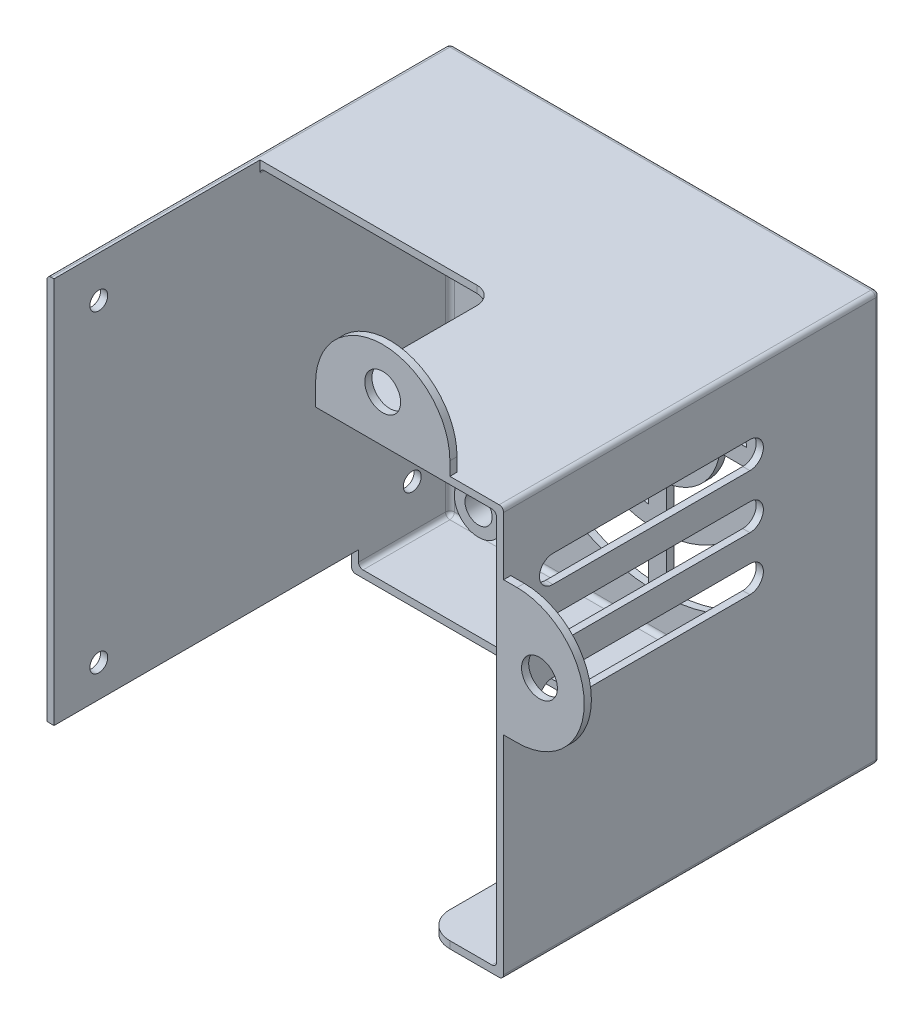
SolidWorks part; units mm, degrees
material "Aleación 1060"
ref_plane "Alzado" through (0, 0, 0) normal (0, 0, 1) x (1, 0, 0)
ref_plane "Planta" through (0, 0, 0) normal (0, 1, 0) x (1, 0, 0)
ref_plane "Vista lateral" through (0, 0, 0) normal (1, 0, 0) x (0, 0, -1)
ref_plane "Plano1" through (0, 0, 42) normal (0, 0, 1) x (1, 0, 0)
sketch "Croquis1" plane through (0, 0, 42) normal (0, 0, 1) x (1, 0, 0)
  line L0 (22.5, 23.6) -> (-25.5, 23.6)
  line L1 (-25.5, 23.6) -> (-25.5, -22.1)
  line L2 (-25.5, -22.1) -> (22.5, -22.1)
  line L3 (22.5, -22.1) -> (22.5, 23.6)
extrude "Saliente-Extruir1" add sketch "Croquis1" against normal blind 42
sketch "Croquis2" plane through (0, 23.6, 0) normal (0, 1, 0) x (-1, 0, 0)
  line L0 (25.5, 42) -> (-1.5, 42)
  line L1 (-1.5, 42) -> (-1.5, 22)
  line L2 (-1.5, 22) -> (25.5, 22)
  line L3 (25.5, 22) -> (25.5, 42)
extrude "Cortar-Extruir1" cut sketch "Croquis2" against normal through all
sketch "Croquis3" plane through (0, 0, 22) normal (0, 0, 1) x (1, 0, 0)
  line L0 (-25.5, 23.6) -> (-24.7, 23.6)
  line L1 (-24.7, 23.6) -> (-24.7, -19.6)
  line L2 (-24.7, -19.6) -> (-25.5, -19.6)
  line L3 (-25.5, -19.6) -> (-25.5, 23.6)
extrude "Saliente-Extruir2" add sketch "Croquis3" along normal blind 23
sketch "Croquis4" plane through (0, 0, 22) normal (0, 0, 1) x (1, 0, 0)
  line L0 (1.5, -22.1) -> (1.5, -19.6)
  line L1 (1.5, -19.6) -> (-25.5, -19.6)
  line L2 (-25.5, -19.6) -> (-25.5, -22.1)
  line L3 (-25.5, -22.1) -> (1.5, -22.1)
extrude "Cortar-Extruir2" cut sketch "Croquis4" against normal blind 11
ref_plane "Plano2" through (0, -19.6, 0) normal (0, -1, 0) x (1, 0, 0)
ref_plane "Plano3" through (0, 22.8, 0) normal (0, 1, 0) x (1, 0, 0)
sketch "Croquis6" plane through (0, 22.8, 0) normal (0, 1, 0) x (1, 0, 0)
  line L0 (1.5, -22) -> (1.5, -11)
  line L1 (1.5, -11) -> (-24.7, -11)
  line L2 (-24.7, -11) -> (-24.7, -22)
  line L3 (-24.7, -22) -> (1.5, -22)
extrude "Cortar-Extruir3" cut sketch "Croquis6" against normal up to surface up to plane "Plano2"
sketch "Croquis7" plane through (1.5, 0, 0) normal (-1, 0, 0) x (0, 0, 1)
  line L0 (42, 22.8) -> (11, 22.8)
  line L1 (11, 22.8) -> (11, -22.1)
  line L2 (11, -22.1) -> (42, -22.1)
  line L3 (42, -22.1) -> (42, 22.8)
extrude "Cortar-Extruir4" cut sketch "Croquis7" against normal blind 12
sketch "Croquis8" plane through (0, 0, 11) normal (0, 0, 1) x (1, 0, 0)
  line L0 (-24.7, -21.3) -> (13.5, -21.3)
  line L1 (13.5, -21.3) -> (13.5, 22.8)
  line L2 (13.5, 22.8) -> (-24.7, 22.8)
  line L3 (-24.7, 22.8) -> (-24.7, -21.3)
extrude "Cortar-Extruir5" cut sketch "Croquis8" against normal blind 10.2
ref_plane "Plano4" through (21.7, 0, 0) normal (1, 0, 0) x (0, 0, -1)
sketch "Croquis9" plane through (21.7, 0, 0) normal (1, 0, 0) x (0, 0, -1)
  line L0 (-0.8, -21.3) -> (-0.8, 22.8)
  line L1 (-0.8, 22.8) -> (-42, 22.8)
  line L2 (-42, 22.8) -> (-42, -21.3)
  line L3 (-42, -21.3) -> (-0.8, -21.3)
extrude "Cortar-Extruir6" cut sketch "Croquis9" against normal up to next
sketch "Croquis10" plane through (0, 0, 0.8) normal (0, 0, 1) x (1, 0, 0)
  line L0 (-0.5, -6.1782) -> (-0.5, -9.1999)
  line L1 (8.4499, -0.25) -> (5.4282, -0.25)
  arc A0 (5.4282, -0.25) -> (-0.5, -6.1782) centre (-1.5, 0.75) cw
  arc A1 (-0.5, -9.1999) -> (8.4499, -0.25) centre (-1.5, 0.75) ccw
extrude "Cortar-Extruir7" cut sketch "Croquis10" against normal through all
sketch "Croquis11" plane through (0, 0, 0.8) normal (0, 0, 1) x (1, 0, 0)
  line L0 (-0.5, -11.2083) -> (-0.5, -17.2222)
  line L1 (16.4722, -0.25) -> (10.4583, -0.25)
  arc A0 (10.4583, -0.25) -> (-0.5, -11.2083) centre (-1.5, 0.75) cw
  arc A1 (-0.5, -17.2222) -> (16.4722, -0.25) centre (-1.5, 0.75) ccw
extrude "Cortar-Extruir8" cut sketch "Croquis11" against normal through all
sketch "Croquis12" plane through (0, 0, 0.8) normal (0, 0, 1) x (1, 0, 0)
  line L0 (-8.4282, -0.25) -> (-11.4499, -0.25)
  line L1 (-2.5, -9.1999) -> (-2.5, -6.1782)
  arc A0 (-2.5, -6.1782) -> (-8.4282, -0.25) centre (-1.5, 0.75) cw
  arc A1 (-11.4499, -0.25) -> (-2.5, -9.1999) centre (-1.5, 0.75) ccw
extrude "Cortar-Extruir9" cut sketch "Croquis12" against normal through all
sketch "Croquis13" plane through (0, 0, 0.8) normal (0, 0, 1) x (1, 0, 0)
  line L0 (-13.4583, -0.25) -> (-19.4722, -0.25)
  line L1 (-2.5, -17.2222) -> (-2.5, -11.2083)
  arc A0 (-2.5, -11.2083) -> (-13.4583, -0.25) centre (-1.5, 0.75) cw
  arc A1 (-19.4722, -0.25) -> (-2.5, -17.2222) centre (-1.5, 0.75) ccw
extrude "Cortar-Extruir10" cut sketch "Croquis13" against normal through all
sketch "Croquis14" plane through (0, 0, 0.8) normal (0, 0, 1) x (1, 0, 0)
  line L0 (-2.5, 7.6782) -> (-2.5, 10.6999)
  line L1 (-11.4499, 1.75) -> (-8.4282, 1.75)
  arc A0 (-8.4282, 1.75) -> (-2.5, 7.6782) centre (-1.5, 0.75) cw
  arc A1 (-2.5, 10.6999) -> (-11.4499, 1.75) centre (-1.5, 0.75) ccw
extrude "Cortar-Extruir11" cut sketch "Croquis14" against normal through all
sketch "Croquis15" plane through (0, 0, 0.8) normal (0, 0, 1) x (1, 0, 0)
  line L0 (-2.5, 12.7083) -> (-2.5, 18.7222)
  line L1 (-19.4722, 1.75) -> (-13.4583, 1.75)
  arc A0 (-13.4583, 1.75) -> (-2.5, 12.7083) centre (-1.5, 0.75) cw
  arc A1 (-2.5, 18.7222) -> (-19.4722, 1.75) centre (-1.5, 0.75) ccw
extrude "Cortar-Extruir12" cut sketch "Croquis15" against normal through all
sketch "Croquis16" plane through (0, 0, 0.8) normal (0, 0, 1) x (1, 0, 0)
  line L0 (5.4282, 1.75) -> (8.4499, 1.75)
  line L1 (-0.5, 10.6999) -> (-0.5, 7.6782)
  arc A0 (-0.5, 7.6782) -> (5.4282, 1.75) centre (-1.5, 0.75) cw
  arc A1 (8.4499, 1.75) -> (-0.5, 10.6999) centre (-1.5, 0.75) ccw
extrude "Cortar-Extruir13" cut sketch "Croquis16" against normal through all
sketch "Croquis17" plane through (22.5, 0, 0) normal (1, 0, 0) x (0, 0, -1)
  line L0 (-36.5, 1.4) -> (-14.5, 1.4)
  line L1 (-14.5, 4.4) -> (-36.5, 4.4)
  arc A0 (-36.5, 4.4) -> (-36.5, 1.4) centre (-36.5, 2.9) ccw
  arc A1 (-14.5, 1.4) -> (-14.5, 4.4) centre (-14.5, 2.9) ccw
extrude "Cortar-Extruir14" cut sketch "Croquis17" against normal up to next
sketch "Croquis18" plane through (22.5, 0, 0) normal (1, 0, 0) x (0, 0, -1)
  line L0 (-36.5, 7.4) -> (-14.5, 7.4)
  line L1 (-14.5, 10.4) -> (-36.5, 10.4)
  arc A0 (-36.5, 10.4) -> (-36.5, 7.4) centre (-36.5, 8.9) ccw
  arc A1 (-14.5, 7.4) -> (-14.5, 10.4) centre (-14.5, 8.9) ccw
extrude "Cortar-Extruir15" cut sketch "Croquis18" against normal up to next
sketch "Croquis19" plane through (22.5, 0, 0) normal (1, 0, 0) x (0, 0, -1)
  line L0 (-36.5, 13.4) -> (-14.5, 13.4)
  line L1 (-14.5, 16.4) -> (-36.5, 16.4)
  arc A0 (-36.5, 16.4) -> (-36.5, 13.4) centre (-36.5, 14.9) ccw
  arc A1 (-14.5, 13.4) -> (-14.5, 16.4) centre (-14.5, 14.9) ccw
extrude "Cortar-Extruir16" cut sketch "Croquis19" against normal up to next
sketch "Croquis20" plane through (0, 0, 0) normal (0, 0, -1) x (-1, 0, 0)
  line L0 (-16.4722, 1.75) -> (-10.4583, 1.75)
  line L1 (0.5, 12.7083) -> (0.5, 18.7222)
  arc A0 (-10.4583, 1.75) -> (0.5, 12.7083) centre (1.5, 0.75) cw
  arc A1 (0.5, 18.7222) -> (-16.4722, 1.75) centre (1.5, 0.75) ccw
extrude "Cortar-Extruir17" cut sketch "Croquis20" against normal through all
sketch "Croquis21" plane through (0, 0, 42) normal (0, 0, 1) x (1, 0, 0)
  line L0 (1.5, 25.1) -> (1.5, 23.6)
  line L1 (1.5, 23.6) -> (16.5, 23.6)
  line L2 (16.5, 23.6) -> (16.5, 25.1)
  arc A0 (16.5, 25.1) -> (1.5, 25.1) centre (9, 25.1) ccw
extrude "Saliente-Extruir3" add sketch "Croquis21" against normal blind 0.8
sketch "Croquis22" plane through (0, 0, 42) normal (0, 0, 1) x (1, 0, 0)
  line L0 (24, 16.6) -> (22.5, 16.6)
  line L1 (22.5, 16.6) -> (22.5, 1.6)
  line L2 (22.5, 1.6) -> (24, 1.6)
  arc A0 (24, 1.6) -> (24, 16.6) centre (24, 9.1) ccw
extrude "Saliente-Extruir4" add sketch "Croquis22" against normal blind 0.8
ref_plane "Plano5" through (0, -15.2, 0) normal (0, -1, 0) x (1, 0, 0)
ref_plane "Plano6" through (0, 16.8, 0) normal (0, -1, 0) x (1, 0, 0)
hole_wizard "Diámetro de taladro Ø2.0 (2)1" positions "Croquis28" profile "Croquis27" hole size "Ø2.0" standard "Ansi Metric"
sketch "Croquis28" plane through (-24.7, 0, 0) normal (1, 0, 0) x (0, 0, -1)
  point P0 (-40, 19)
  point P1 (-40, -16)
  point P2 (-5, -16)
  point P3 (-5, 19)
sketch "Croquis27" plane through (-24.7, 19, 40) normal (0, 1, 0) x (0, 0, -1)
  line L0 (0, 0) -> (0, 0.8)
  line L1 (0, 0.8) -> (1, 0.8)
  line L2 (1, 0.8) -> (1, 0)
  line L5 (1, 0) -> (0, 0)
  line L11 (0, -6.35) -> (0, 107.95) construction
  dimension "Diámetro de taladro hasta el siguiente" = 2
  dimension "Profundidad de taladro hasta el siguiente" = 0.8
hole_wizard "Diámetro de taladro Ø4.0 (4)1" positions "Croquis30" profile "Croquis29" hole size "Ø4.0" standard "Ansi Metric"
sketch "Croquis30" plane through (0, 0, 42) normal (0, 0, 1) x (1, 0, 0)
  point P0 (9, 28)
  point P1 (26.5, 9.1)
sketch "Croquis29" plane through (9, 28, 42) normal (1, 0, 0) x (0, -1, 0)
  line L0 (0, 0) -> (0, 42)
  line L1 (0, 42) -> (2, 42)
  line L2 (2, 42) -> (2, 0)
  line L5 (2, 0) -> (0, 0)
  line L11 (0, -6.35) -> (0, 107.95) construction
  dimension "Diámetro de taladro hasta el siguiente" = 4
  dimension "Profundidad de taladro hasta el siguiente" = 42
fillet "Redondeo1" radius 0.5 16 edges at (21.7, -21.3, 21.4) (21.7, 22.8, 21.4) (21.7, 0.75, 0.8) (-1.5, -21.3, 0.8) (-24.7, -21.3, 5.9) (-1.5, 22.8, 0.8) (-24.7, 0.75, 0.8) (-24.7, 22.8, 11.4) (22.5, -22.1, 21) (-25.5, 23.6, 22.5) (22.5, 0.75, 0) (-1.5, 23.6, 0) (22.5, 23.6, 21) (-25.5, 0.75, 0) (-1.5, -22.1, 0) (-25.5, -22.1, 5.5)
fillet "Redondeo2" radius 2 1 edges at (1.5, 23.2, 22)
fillet "Redondeo3" radius 3 2 edges at (13.5, -21.7, 11) (13.5, -21.7, 42)
sketch "Croquis33" plane through (0, 0, 0.8) normal (0, 0, 1) x (1, 0, 0)
  circle A0 centre (-17.5, 16.8) radius 1.5
  circle A1 centre (-17.5, 16.8) radius 2.7
  circle A2 centre (14.5, 16.8) radius 1.5
  circle A3 centre (14.5, 16.8) radius 2.7
  circle A4 centre (-17.5, -15.2) radius 1.5168
  circle A5 centre (-17.5, -15.2) radius 2.7
  circle A6 centre (14.5, -15.2) radius 1.5
  circle A7 centre (14.5, -15.2) radius 2.7
extrude "Saliente-Extruir5" add sketch "Croquis33" along normal blind 4 separate body
